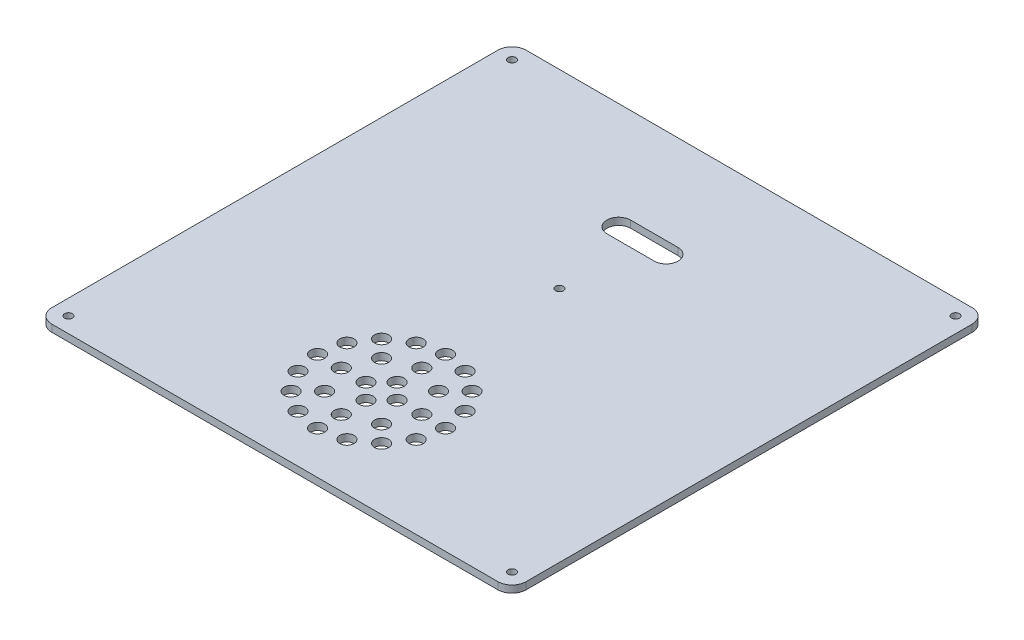
SolidWorks part; units mm, degrees
ref_plane "Front Plane" through (0, 0, 0) normal (0, 0, 1) x (1, 0, 0)
ref_plane "Top Plane" through (0, 0, 0) normal (0, 1, 0) x (1, 0, 0)
ref_plane "Right Plane" through (0, 0, 0) normal (1, 0, 0) x (0, 0, -1)
sketch "Sketch1" plane through (0, 0, 0) normal (0, 1, 0) x (1, 0, 0)
  line L0 (116.9749, 45) -> (126.9749, 45) construction
  line L1 (0, 0) -> (200, 0)
  line L2 (0, 0) -> (0, 200)
  line L3 (0, 200) -> (200, 200)
  line L4 (200, 0) -> (200, 200)
  line L5 (116.9749, 45) -> (100, 45) construction
  circle A0 centre (100, 45) radius 36 construction
  circle A1 centre (116.9749, 45) radius 3
  circle A2 centre (112.003, 32.997) radius 3
  circle A3 centre (100, 28.0251) radius 3
  circle A4 centre (87.997, 32.997) radius 3
  circle A5 centre (83.0251, 45) radius 3
  circle A6 centre (87.997, 57.003) radius 3
  circle A7 centre (100, 61.9749) radius 3
  circle A8 centre (112.003, 57.003) radius 3
  circle A9 centre (126.9749, 45) radius 3
  circle A10 centre (124.9219, 34.679) radius 3
  circle A11 centre (119.0755, 25.9293) radius 3
  circle A12 centre (110.3258, 20.083) radius 3
  circle A13 centre (100.0049, 18.03) radius 3
  circle A14 centre (89.6839, 20.083) radius 3
  circle A15 centre (80.9342, 25.9293) radius 3
  circle A16 centre (75.0878, 34.679) radius 3
  circle A17 centre (106.5596, 45) radius 3
  circle A18 centre (100, 38.4404) radius 3
  circle A19 centre (93.4404, 45) radius 3
  circle A20 centre (100, 51.5596) radius 3
  circle A21 centre (73.0349, 45) radius 3
  circle A22 centre (75.0878, 55.321) radius 3
  circle A23 centre (80.9342, 64.0707) radius 3
  circle A24 centre (89.6839, 69.917) radius 3
  circle A25 centre (100.0049, 71.97) radius 3
  circle A26 centre (110.3258, 69.917) radius 3
  circle A27 centre (119.0755, 64.0707) radius 3
  circle A28 centre (124.9219, 55.321) radius 3
  point P26 (100, 45)
  point P43 (100.0049, 45)
  point P53 (100, 45)
  dimension "D1" = 8
  dimension "D2" = 16
  dimension "D3" = 4
extrude "Boss-Extrude1" add sketch "Sketch1" along normal blind 3
fillet "Fillet1" radius 6 1 edges at (0, 1.5, -200)
fillet "Fillet2" radius 6 1 edges at (200, 1.5, -200)
fillet "Fillet3" radius 6 1 edges at (200, 1.5, 0)
fillet "Fillet4" radius 6 1 edges at (0, 1.5, 0)
sketch "Sketch2" plane through (0, 3, 0) normal (0, 1, 0) x (1, 0, 0)
  line L0 (100, 200) -> (100, -37.3926) construction
  line L1 (194, 200) -> (6, 200) construction
  line L2 (0, 100) -> (254.8165, 100) construction
  line L3 (0, 194) -> (0, 6) construction
  line L4 (110, 160) -> (90, 160)
  line L5 (90, 150) -> (110, 150)
  circle A0 centre (6.5, 193.5) radius 1.65
  circle A1 centre (193.5, 193.5) radius 1.65
  circle A2 centre (6.5, 6.5) radius 1.65
  circle A3 centre (193.5, 6.5) radius 1.65
  circle A4 centre (100, 120) radius 1.65
  circle A5 centre (100, 155) radius 5 construction
  circle A6 centre (90, 155) radius 5
  circle A7 centre (110, 155) radius 5
  point P27 (100, 160)
  point P30 (100, 150)
  dimension "D1" = 6.5
  dimension "D2" = 6.5
  dimension "D3" = 80
  dimension "D4" = 45
extrude "Cut-Extrude1" cut sketch "Sketch2" against normal through all contours A2 | A3 | A1 | A6 | L5 A7 L4 A6 | A7 | A4 | A0
